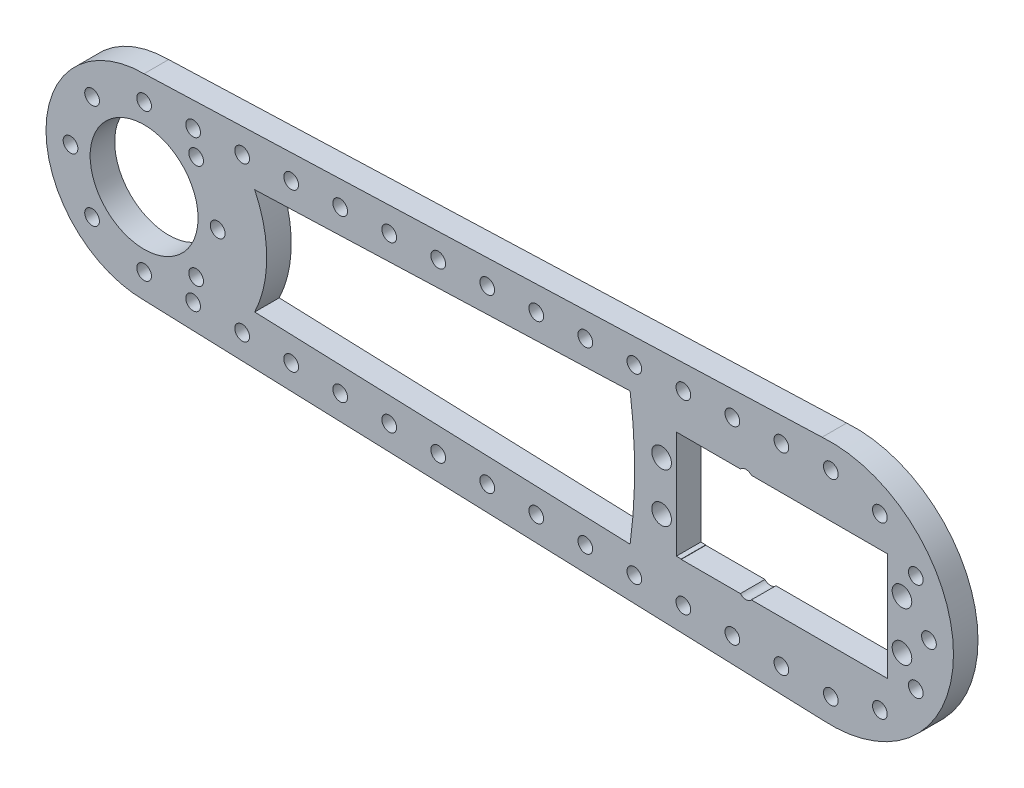
SolidWorks part; units mm, degrees
ref_plane "前视基准面" through (0, 0, 0) normal (0, 0, 1) x (1, 0, 0)
ref_plane "上视基准面" through (0, 0, 0) normal (0, 1, 0) x (1, 0, 0)
ref_plane "右视基准面" through (0, 0, 0) normal (1, 0, 0) x (0, 0, -1)
other "Configuration Table"
sketch "草图1" plane through (0, 0, 0) normal (0, 0, 1) x (1, 0, 0)
  line L0 (0, 0) -> (140, 0)
  line L1 (0, 35) -> (140, 25)
  line L2 (0, -35) -> (140, -25)
  circle A0 centre (0, 0) radius 35
  circle A1 centre (140, 0) radius 25
  dimension "D1" = 70
  dimension "D3" = 50
  dimension "D2" = 140
extrude "凸台-拉伸3" add sketch "草图1" along normal blind 5
sketch "草图4" plane through (0, 0, 5) normal (0, 0, 1) x (1, 0, 0)
  line L1 (-5, -5) -> (5, -5)
  line L2 (-5, -5) -> (-5, 5)
  line L3 (-5, 5) -> (5, 5)
  line L4 (5, -5) -> (5, 5)
  line L5 (-5, -5) -> (5, 5) construction
  line L6 (-5, 5) -> (5, -5) construction
  line L7 (135, -5) -> (145, -5)
  line L8 (135, -5) -> (135, 5)
  line L9 (135, 5) -> (145, 5)
  line L10 (145, -5) -> (145, 5)
  line L11 (135, -5) -> (145, 5) construction
  line L12 (135, 5) -> (145, -5) construction
  circle A0 centre (0, 0) radius 4
  circle A1 centre (-5, 5) radius 1.5
  circle A2 centre (5, 5) radius 1.5
  circle A3 centre (5, -5) radius 1.5
  circle A4 centre (-5, -5) radius 1.5
  circle A5 centre (140, 0) radius 4
  circle A6 centre (135, 5) radius 1.5
  circle A7 centre (145, 5) radius 1.5
  circle A8 centre (145, -5) radius 1.5
  circle A9 centre (135, -5) radius 1.5
  dimension "D1" = 8
  dimension "D4" = 3
  dimension "D6" = 8
  dimension "D9" = 3
  dimension "D2" = 10
  dimension "D3" = 10
  dimension "D7" = 10
  dimension "D8" = 10
  dimension "D5" = 4
  dimension "D10" = 4
extrude "切除-拉伸3" cut sketch "草图4" against normal blind 5 contours A5 | A0 | L2 A4 L1 | L1 A4 L2 | A6 | A9 | A8 | A7 | A1 | A2 | A3
sketch "草图5" plane through (0, 0, 5) normal (0, 0, 1) x (1, 0, 0)
  circle A0 centre (0, 0) radius 11
  circle A1 centre (140, 0) radius 11
  dimension "D1" = 22
  dimension "D2" = 22
extrude "切除-拉伸4" cut sketch "草图5" against normal blind 2
sketch "草图6" plane through (0, 0, 5) normal (0, 0, 1) x (1, 0, 0)
  circle A0 centre (0, 0) radius 30
  circle A1 centre (0, 30) radius 1.5
  circle A2 centre (15, 25.9808) radius 1.5
  circle A3 centre (25.9808, 15) radius 1.5
  circle A4 centre (30, 0) radius 1.5
  circle A5 centre (25.9808, -15) radius 1.5
  circle A6 centre (15, -25.9808) radius 1.5
  circle A7 centre (0, -30) radius 1.5
  circle A8 centre (-15, -25.9808) radius 1.5
  circle A9 centre (-25.9808, -15) radius 1.5
  circle A10 centre (-30, 0) radius 1.5
  circle A11 centre (-25.9808, 15) radius 1.5
  circle A12 centre (-15, 25.9808) radius 1.5
  circle A13 centre (140, 0) radius 20
  circle A14 centre (140, 20) radius 1.5
  circle A15 centre (150, 17.3205) radius 1.5
  circle A16 centre (157.3205, 10) radius 1.5
  circle A17 centre (160, 0) radius 1.5
  circle A18 centre (157.3205, -10) radius 1.5
  circle A19 centre (150, -17.3205) radius 1.5
  circle A20 centre (140, -20) radius 1.5
  circle A21 centre (130, -17.3205) radius 1.5
  circle A22 centre (122.6795, -10) radius 1.5
  circle A23 centre (120, 0) radius 1.5
  circle A24 centre (122.6795, 10) radius 1.5
  circle A25 centre (130, 17.3205) radius 1.5
  point P29 (0, 0)
  dimension "D1" = 60
  dimension "D2" = 3
  dimension "D4" = 40
  dimension "D5" = 3
  dimension "D3" = 12
  dimension "D6" = 12
extrude "切除-拉伸6" cut sketch "草图6" against normal through all contours A0 A12 | A11 | A1 | A2 | A3 | A4 | A5 | A6 | A7 | A8 | A9 | A10 | A25 | A14 | A15 | A16 | A17 | A18 | A19 | A20 | A21 | A22 | A23 | A24
sketch "草图7" plane through (0, 0, 5) normal (0, 0, 1) x (1, 0, 0)
  line L0 (140, 25) -> (0, 20)
  line L1 (140, -25) -> (0, -20)
  circle A0 centre (0, 0) radius 20
  circle A1 centre (140, 0) radius 25
  circle M1 centre (15, -25.9808) radius 1.5
  circle M2 centre (0, -30) radius 1.5
  circle M3 centre (-15, -25.9808) radius 1.5
  circle M4 centre (-25.9808, -15) radius 1.5
  circle M5 centre (-30, 0) radius 1.5
  circle M20 centre (15, 25.9808) radius 1.5
  circle M21 centre (-15, 25.9808) radius 1.5
  circle M22 centre (-25.9808, 15) radius 1.5
  circle M23 centre (0, 30) radius 1.5
  line M27 (0, -35) -> (140, -25)
  line M29 (140, 25) -> (0, 35)
  arc M30 (0, 35) -> (0, -35) centre (0, 0) ccw
  dimension "D1" = 40
extrude "切除-拉伸7" cut sketch "草图7" against normal blind 10 contours A1 L1 A0 L0 M29 M30 M27 M1 M3 M5 M21 M23 M22 M20 M4 M2
sketch "草图8" plane through (0, 0, 5) normal (0, 0, 1) x (1, 0, 0)
  circle A1 centre (0, 0) radius 11
extrude "切除-拉伸8" cut sketch "草图8" against normal blind 10
sketch "草图9" plane through (0, 0, 5) normal (0, 0, 1) x (1, 0, 0)
  circle A0 centre (0, 0) radius 15
  circle A1 centre (0, 15) radius 1.5
  circle A2 centre (10.6066, 10.6066) radius 1.5
  circle A3 centre (15, 0) radius 1.5
  circle A4 centre (10.6066, -10.6066) radius 1.5
  circle A5 centre (0, -15) radius 1.5
  circle A6 centre (-10.6066, -10.6066) radius 1.5
  circle A7 centre (-15, 0) radius 1.5
  circle A8 centre (-10.6066, 10.6066) radius 1.5
  dimension "D1" = 30
  dimension "D2" = 3
  dimension "D3" = 8
extrude "切除-拉伸9" cut sketch "草图9" against normal blind 10 contours A0 A4 | A2 | A3 | A5 | A6 | A7 | A8 | A1
sketch "草图10" plane through (0, 0, 3) normal (0, 0, 1) x (1, 0, 0)
  circle A0 centre (140, 0) radius 5
  dimension "D1" = 10
extrude "切除-拉伸10" cut sketch "草图10" against normal blind 10
sketch "草图11" plane through (0, 0, 5) normal (0, 0, 1) x (1, 0, 0)
  line L0 (140, 0) -> (110, 0)
  line L1 (140, 0) -> (130, 0)
  line L2 (110, 0) -> (105.5, 0)
  line L3 (150, -10) -> (110, -10)
  line L4 (150, -10) -> (150, 10)
  line L5 (150, 10) -> (110, 10)
  line L6 (110, -10) -> (110, 10)
  line L7 (150, -10) -> (110, 10) construction
  line L8 (150, 10) -> (110, -10) construction
  line L9 (105.5, 0) -> (105.5, 5)
  line L10 (130, -1000) -> (130, 49000) construction
  circle A0 centre (105.5, 5) radius 2
  circle A1 centre (105.5, -5) radius 2
  circle A2 centre (154.5, -5) radius 2
  circle A3 centre (154.5, 5) radius 2
  dimension "D6" = 4
  dimension "D1" = 30
  dimension "D2" = 10
  dimension "D3" = 20
  dimension "D4" = 4.5
  dimension "D5" = 5
extrude "切除-拉伸11" cut sketch "草图11" against normal blind 10
sketch "草图12" plane through (0, 0, 5) normal (0, 0, 1) x (1, 0, 0)
  line L0 (110, 10) -> (44831.3595, -22350.6798) construction
  line L1 (150, 10) -> (-44571.3595, -22350.6798) construction
  line L3 (109.5, -11) -> (150.5, -11)
  line L4 (109.5, -11) -> (109.5, 11)
  line L5 (109.5, 11) -> (150.5, 11)
  line L6 (150.5, -11) -> (150.5, 11)
  line L7 (109.5, -11) -> (150.5, 11) construction
  line L8 (109.5, 11) -> (150.5, -11) construction
  point P8 (130, 0)
  dimension "D1" = 41
  dimension "D2" = 22
extrude "切除-拉伸12" cut sketch "草图12" against normal blind 10
sketch "草图13" plane through (0, 0, 5) normal (0, 0, 1) x (1, 0, 0)
  line L0 (0.1785, -15.0032) -> (138.395, -19.9395)
  line L1 (0, -20) -> (138.2166, -24.9363)
  circle A0 centre (0, -15) radius 1.5
  circle A1 centre (9.9936, -15.3569) radius 1.5
  circle A2 centre (19.9873, -15.7138) radius 1.5
  circle A3 centre (29.9809, -16.0707) radius 1.5
  circle A4 centre (39.9745, -16.4277) radius 1.5
  circle A5 centre (49.9681, -16.7846) radius 1.5
  circle A6 centre (59.9618, -17.1415) radius 1.5
  circle A7 centre (69.9554, -17.4984) radius 1.5
  circle A8 centre (79.949, -17.8553) radius 1.5
  circle A9 centre (89.9427, -18.2122) radius 1.5
  circle A10 centre (99.9363, -18.5692) radius 1.5
  circle A11 centre (109.9299, -18.9261) radius 1.5
  circle A12 centre (119.9235, -19.283) radius 1.5
  circle A13 centre (129.9172, -19.6399) radius 1.5
  circle A14 centre (139.9108, -19.9968) radius 1.5
  circle M27 centre (130, -17.3205) radius 1.5
  dimension "D1" = 5
  dimension "D2" = 15
extrude "切除-拉伸13" cut sketch "草图13" against normal blind 10 contours L0 A1 | L0 A1 | L0 A13 | A13 L0 M27 | A2 | A3 | A4 | A5 | A6 | A7 | A9 | A8 | A10 | A11 | A12
sketch "草图14" plane through (0, 0, 5) normal (0, 0, 1) x (1, 0, 0)
  circle A0 centre (130, -17.3205) radius 1.5
  circle A1 centre (129.9172, -19.6399) radius 1.5
extrude "凸台-拉伸4" add sketch "草图14" against normal blind 5 contours A1 A0
sketch "草图15" plane through (0, 0, 5) normal (0, 0, 1) x (1, 0, 0)
  circle A0 centre (25.9808, 15) radius 1.5
  circle A1 centre (30, 0) radius 1.5
  circle A2 centre (25.9808, -15) radius 1.5
extrude "凸台-拉伸6" add sketch "草图15" against normal blind 5
sketch "草图16" plane through (0, 0, 5) normal (0, 0, 1) x (1, 0, 0)
  line L0 (0, 20) -> (140, 25)
  line L1 (0.1785, 15.0032) -> (140.1785, 20.0032)
  arc A0 (138.2166, -24.9363) -> (138.2166, 24.9363) centre (140, 0) ccw construction
  circle A1 centre (0, 15) radius 1.5
  circle A2 centre (9.9936, 15.3569) radius 1.5
  circle A3 centre (19.9873, 15.7138) radius 1.5
  circle A4 centre (29.9809, 16.0707) radius 1.5
  circle A5 centre (39.9745, 16.4277) radius 1.5
  circle A6 centre (49.9681, 16.7846) radius 1.5
  circle A7 centre (59.9618, 17.1415) radius 1.5
  circle A8 centre (69.9554, 17.4984) radius 1.5
  circle A9 centre (79.949, 17.8553) radius 1.5
  circle A10 centre (89.9427, 18.2122) radius 1.5
  circle A11 centre (99.9363, 18.5692) radius 1.5
  circle A12 centre (109.9299, 18.9261) radius 1.5
  circle A13 centre (119.9235, 19.283) radius 1.5
  circle A14 centre (129.9172, 19.6399) radius 1.5
  circle A15 centre (139.9108, 19.9968) radius 1.5
  dimension "D1" = 5
  dimension "D2" = 15
extrude "切除-拉伸14" cut sketch "草图16" against normal blind 5 contours L1 A6 | L1 A6 | L1 A7 | L1 A7 | L1 A8 | L1 A8 | A2 | A3 | A4 | A5 | A9 | A10 | A11 | A12 | A13 | A14
sketch "草图17" plane through (0, 0, 5) normal (0, 0, 1) x (1, 0, 0)
  circle A0 centre (130, 17.3205) radius 1.5
  circle A1 centre (129.9172, 19.6399) radius 1.5
extrude "凸台-拉伸7" add sketch "草图17" against normal blind 5 contours A1 A0
sketch "草图18" plane through (0, 0, 5) normal (0, 0, 1) x (1, 0, 0)
  line L2 (138.5735, 14.9427) -> (0.3569, 10.0064)
  line L3 (138.5735, 14.9427) -> (0.3569, 10.0064)
  line L5 (138.5735, -14.9427) -> (0.3569, -10.0064)
  line L6 (138.5735, -14.9427) -> (0.3569, -10.0064)
  circle A0 centre (0, 0) radius 25
  circle A1 centre (0, 0) radius 100
  dimension "D1" = 50
  dimension "D2" = 200
  dimension "D3" = 10
  dimension "D4" = 10
extrude "切除-拉伸15" cut sketch "草图18" against normal blind 5 contours L6 A1 L3 A0
sketch "草图19" plane through (0, 0, 5) normal (0, 0, 1) x (1, 0, 0)
  line L1 (109.5, 11) -> (108.5, 11)
  line L2 (109.5, 11) -> (109.5, -10.9322)
  line L3 (109.5, -10.9322) -> (108.5, -10.9322)
  line L4 (108.5, 11) -> (108.5, -10.9322)
  line L5 (150.5, 11) -> (151.5, 11)
  line L6 (150.5, 11) -> (150.5, -11)
  line L7 (150.5, -11) -> (151.5, -11)
  line L8 (151.5, 11) -> (151.5, -11)
  dimension "D1" = 1
  dimension "D2" = 1
extrude "切除-拉伸16" cut sketch "草图19" against normal blind 10
